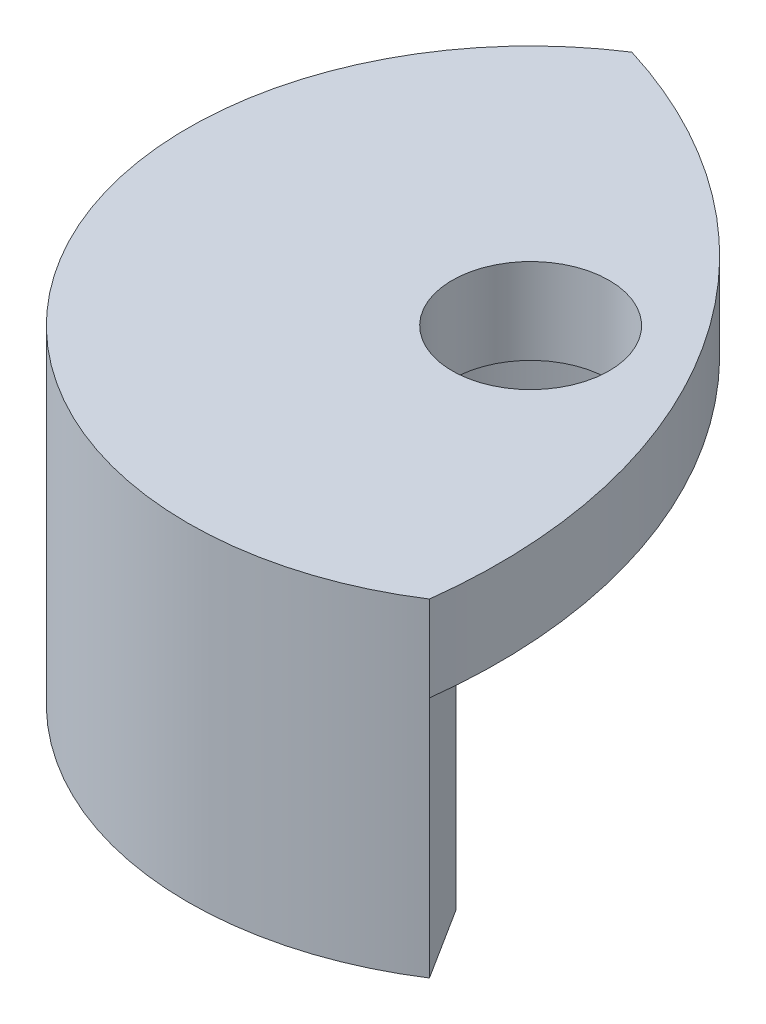
SolidWorks part; units mm, degrees
ref_plane "前视基准面" through (0, 0, 0) normal (0, 0, 1) x (1, 0, 0)
ref_plane "上视基准面" through (0, 0, 0) normal (0, 1, 0) x (1, 0, 0)
ref_plane "右视基准面" through (0, 0, 0) normal (1, 0, 0) x (0, 0, -1)
sketch "草图2" plane through (0, 0, 0) normal (0, 1, 0) x (1, 0, 0)
  line L0 (-13.0506, 20.1416) -> (-8.2391, 12.5346)
  line L1 (8.2391, -12.5346) -> (13.0506, -20.1416)
  arc A2 (-8.2391, 12.5346) -> (8.2391, -12.5346) centre (0, 0) ccw
  arc A3 (-13.0506, 20.1416) -> (13.0506, -20.1416) centre (0, 0) ccw
  dimension "D1" = 15
  dimension "D2" = 24
extrude "凸台-拉伸2" add sketch "草图2" along normal blind 17
sketch "草图4" plane through (0, 17, 0) normal (0, 1, 0) x (1, 0, 0)
  arc A0 (13.0506, -20.1416) -> (-13.0506, 20.1416) centre (0, 0) cw
  arc A1 (13.0506, -20.1416) -> (-13.0506, 20.1416) centre (-23.9992, -15.5501) ccw
extrude "凸台-拉伸3" add sketch "草图4" along normal blind 6
sketch "草图5" plane through (0, 23, 0) normal (0, 1, 0) x (1, 0, 0)
  circle A1 centre (0, 0) radius 4.5
  arc A2 (-8.2391, 12.5346) -> (8.2391, -12.5346) centre (0, 0) ccw construction
  dimension "D1" = 9
extrude "切除-拉伸1" cut sketch "草图5" against normal blind 6
sketch "草图7" plane through (0, 0, 0) normal (0, -1, 0) x (1, 0, 0)
  line L2 (0, 0) -> (-17.4234, -8.7565) construction
  line L4 (-16.295, 10.7108) -> (0, 0) construction
  line L5 (1.1283, 19.4673) -> (0, 0) construction
  line L6 (8.2391, 12.5346) -> (0, 0) construction
  circle A3 centre (-17.4234, -8.7565) radius 1.3
  circle A4 centre (-16.295, 10.7108) radius 1.3
  circle A5 centre (1.1283, 19.4673) radius 1.3
  arc A6 (-11.1788, -15.9776) -> (7.303, 18.0808) centre (0, 0) cw construction
  arc A7 (8.2391, 12.5346) -> (-8.2391, -12.5346) centre (0, 0) ccw construction
  dimension "D1" = 19.5
  dimension "D2" = 2.6
  dimension "D5" = 2.6
  dimension "D6" = 2.6
  dimension "D3" = 60
  dimension "D4" = 60
extrude "切除-拉伸2" cut sketch "草图7" against normal blind 10
sketch "Sketch1" plane through (0, 17, 0) normal (0, -1, 0) x (1, 0, 0)
  circle A0 centre (0, 0) radius 5.5
  dimension "D1" = 11
extrude "Cut-Extrude1" cut sketch "Sketch1" against normal through all
sketch "草图8" plane through (0, 0, 0) normal (0, -1, 0) x (1, 0, 0)
  line L2 (8.2391, 12.5346) -> (13.0506, 20.1416)
  line L3 (-13.0506, -20.1416) -> (-8.2391, -12.5346)
  line L4 (8.2391, 12.5346) -> (13.0506, 20.1416)
  line L5 (-13.0506, -20.1416) -> (-8.2391, -12.5346)
  circle A0 centre (-17.4234, -8.7565) radius 1.3 construction
  circle A1 centre (1.1283, 19.4673) radius 1.3 construction
  arc A2 (8.2391, 12.5346) -> (-8.2391, -12.5346) centre (0, 0) ccw
  arc A3 (13.0506, 20.1416) -> (-13.0506, -20.1416) centre (0, 0) ccw
  arc A4 (8.2391, 12.5346) -> (-8.2391, -12.5346) centre (0, 0) ccw
  arc A5 (13.0506, 20.1416) -> (-13.0506, -20.1416) centre (0, 0) ccw
  circle A6 centre (-16.295, 10.7108) radius 1.3 construction
  circle A7 centre (-17.4234, -8.7565) radius 1.3
  circle A8 centre (1.1283, 19.4673) radius 1.3
  circle A9 centre (-16.295, 10.7108) radius 1.3
  dimension "D1" = 0
sketch "草图9" plane through (0, 23, 0) normal (0, 1, 0) x (1, 0, 0)
  line L5 (59.9341, 22.1285) -> (76.224, 24.9468)
  line L6 (76.224, 24.9468) -> (89.4228, 18.2288)
  line L7 (89.4228, 18.2288) -> (91.8661, 3.2236)
  line L8 (91.8661, 3.2236) -> (83.6771, -6.4365)
  line L9 (83.6771, -6.4365) -> (49.4814, -12.3526)
  line L10 (49.4814, -12.3526) -> (13.0506, -20.1416)
  line L11 (-13.0506, 20.1416) -> (59.9341, 22.1285)
  arc A0 (13.0506, -20.1416) -> (-13.0506, 20.1416) centre (-23.9992, -15.5501) ccw construction
  arc A1 (13.0506, -20.1416) -> (-13.0506, 20.1416) centre (-23.9992, -15.5501) ccw
sketch "草图10" plane through (0, 17, 0) normal (0, -1, 0) x (1, 0, 0)
  circle A0 centre (0, 0) radius 18
extrude "切除-拉伸3" cut sketch "草图10" along normal up to surface (17 mm away)
